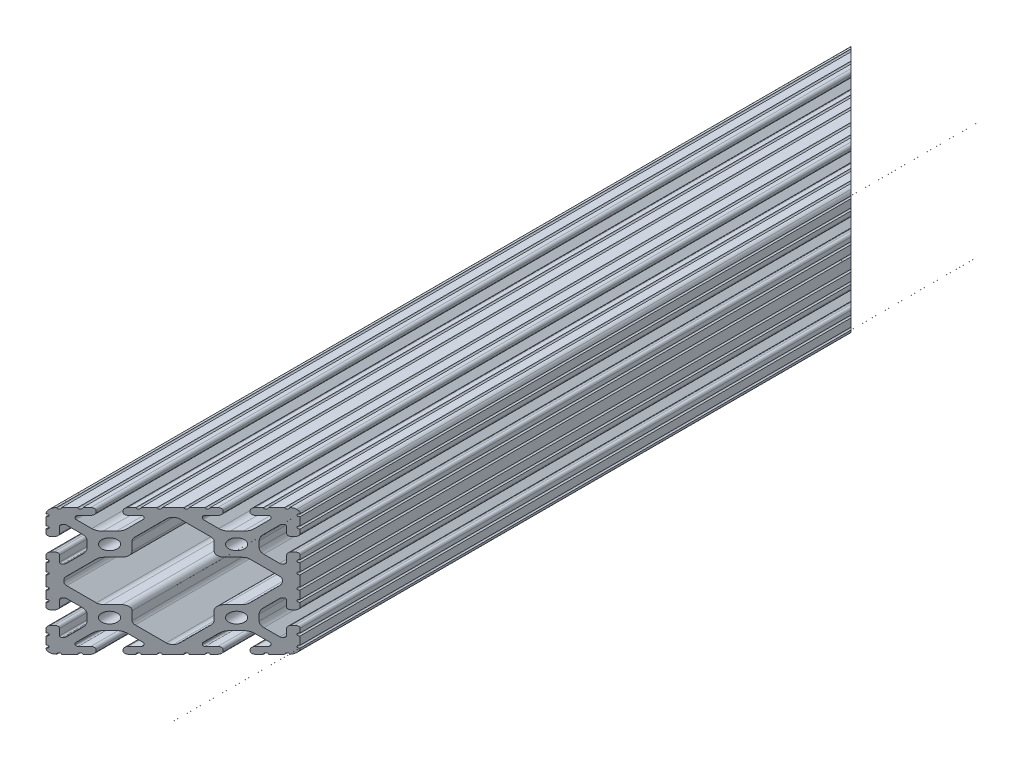
SolidWorks part; units mm, degrees
material "6061-T6 (SS)"
ref_plane "Front" through (0, 0, 0) normal (0, 0, 1) x (1, 0, 0)
ref_plane "Top" through (0, 0, 0) normal (0, 1, 0) x (1, 0, 0)
ref_plane "Right" through (0, 0, 0) normal (1, 0, 0) x (0, 0, -1)
ref_plane "Plane1" through (0, 0, -609.6) normal (0, 0, -1) x (-1, 0, 0)
sketch "Sketch1" plane through (0, 0, -609.6) normal (0, 0, -1) x (-1, 0, 0)
  line L0 (31.9021, -2.4756) -> (23.0141, -11.3637)
  line L1 (20.769, -12.2936) -> (15.4686, -12.2936)
  line L2 (12.2936, -15.4686) -> (12.2936, -20.5983)
  line L3 (11.3637, -22.8433) -> (2.0515, -32.1555)
  line L4 (-2.0515, -32.1555) -> (-11.3637, -22.8433)
  line L5 (-12.2936, -20.5983) -> (-12.2936, -15.4686)
  line L6 (-15.4686, -12.2936) -> (-20.769, -12.2936)
  line L7 (-23.0141, -11.3637) -> (-31.9021, -2.4756)
  line L8 (-31.9021, 2.4756) -> (-23.0141, 11.3637)
  line L9 (-20.769, 12.2936) -> (-15.4686, 12.2936)
  line L10 (-12.2936, 15.4686) -> (-12.2936, 20.5983)
  line L11 (-11.3637, 22.8433) -> (-2.0515, 32.1555)
  line L12 (2.0515, 32.1555) -> (11.3637, 22.8433)
  line L13 (12.2936, 20.5983) -> (12.2936, 15.4686)
  line L14 (15.4686, 12.2936) -> (20.769, 12.2936)
  line L15 (23.0141, 11.3637) -> (31.9021, 2.4756)
  line L16 (36.5252, -23.0554) -> (35.6108, -23.0554)
  line L17 (34.036, -24.6302) -> (34.036, -28.448)
  line L18 (33.147, -29.337) -> (32.6643, -29.337)
  line L19 (32.0357, -29.0766) -> (27.1976, -24.2385)
  line L20 (25.8064, -20.8799) -> (25.8064, -17.2201)
  line L21 (27.1976, -13.8615) -> (31.9489, -9.1101)
  line L22 (32.7869, -8.763) -> (33.0603, -8.763)
  line L23 (34.036, -9.7387) -> (34.036, -13.4698)
  line L24 (35.6108, -15.0446) -> (36.5252, -15.0446)
  line L25 (38.1, -13.4698) -> (38.1, -11.075)
  line L26 (38.1, -9.552) -> (38.1, -4.7238)
  line L27 (38.1, -3.2007) -> (38.1, 3.2007)
  line L28 (38.1, 4.7238) -> (38.1, 9.552)
  line L29 (38.1, 11.075) -> (38.1, 13.4698)
  line L30 (36.5252, 15.0446) -> (35.6108, 15.0446)
  line L31 (34.036, 13.4698) -> (34.036, 9.7387)
  line L32 (33.0603, 8.763) -> (32.7869, 8.763)
  line L33 (31.9489, 9.1101) -> (27.1976, 13.8615)
  line L34 (25.8064, 17.2201) -> (25.8064, 20.8799)
  line L35 (27.1976, 24.2385) -> (32.0357, 29.0766)
  line L36 (32.6643, 29.337) -> (33.147, 29.337)
  line L37 (34.036, 28.448) -> (34.036, 24.6302)
  line L38 (35.6108, 23.0554) -> (36.5252, 23.0554)
  line L39 (38.1, 24.6302) -> (38.1, 27.0238)
  line L40 (38.1, 28.5453) -> (38.1, 33.373)
  line L41 (33.4288, 38.1) -> (28.6011, 38.1)
  line L42 (27.0772, 38.1) -> (24.6888, 38.1)
  line L43 (23.114, 36.5252) -> (23.114, 35.6108)
  line L44 (24.6888, 34.036) -> (28.448, 34.036)
  line L45 (29.337, 33.147) -> (29.337, 32.7207)
  line L46 (29.1002, 31.8885) -> (24.4093, 27.1976)
  line L47 (21.0507, 25.8064) -> (17.0493, 25.8064)
  line L48 (13.6907, 27.1976) -> (9.0234, 31.8649)
  line L49 (8.763, 32.4935) -> (8.763, 33.147)
  line L50 (9.652, 34.036) -> (13.4112, 34.036)
  line L51 (14.986, 35.6108) -> (14.986, 36.5252)
  line L52 (13.4112, 38.1) -> (11.1289, 38.1)
  line L53 (9.6053, 38.1) -> (4.7773, 38.1)
  line L54 (3.2537, 38.1) -> (-3.2537, 38.1)
  line L55 (-4.7773, 38.1) -> (-9.6053, 38.1)
  line L56 (-11.1289, 38.1) -> (-13.4112, 38.1)
  line L57 (-14.986, 36.5252) -> (-14.986, 35.6108)
  line L58 (-13.4112, 34.036) -> (-9.652, 34.036)
  line L59 (-8.763, 33.147) -> (-8.763, 32.4935)
  line L60 (-9.0234, 31.8649) -> (-13.6907, 27.1976)
  line L61 (-17.0493, 25.8064) -> (-21.0507, 25.8064)
  line L62 (-24.4093, 27.1976) -> (-29.1002, 31.8885)
  line L63 (-29.337, 32.7207) -> (-29.337, 33.147)
  line L64 (-28.448, 34.036) -> (-24.6888, 34.036)
  line L65 (-23.114, 35.6108) -> (-23.114, 36.5252)
  line L66 (-24.6888, 38.1) -> (-27.0772, 38.1)
  line L67 (-28.6011, 38.1) -> (-33.4288, 38.1)
  line L68 (-38.1, 33.373) -> (-38.1, 28.5453)
  line L69 (-38.1, 27.0238) -> (-38.1, 24.6302)
  line L70 (-36.5252, 23.0554) -> (-35.6108, 23.0554)
  line L71 (-34.036, 24.6302) -> (-34.036, 28.448)
  line L72 (-33.147, 29.337) -> (-32.6643, 29.337)
  line L73 (-32.0357, 29.0766) -> (-27.1976, 24.2385)
  line L74 (-25.8064, 20.8799) -> (-25.8064, 17.2201)
  line L75 (-27.1976, 13.8615) -> (-31.9489, 9.1101)
  line L76 (-32.7869, 8.763) -> (-33.0603, 8.763)
  line L77 (-34.036, 9.7387) -> (-34.036, 13.4698)
  line L78 (-35.6108, 15.0446) -> (-36.5252, 15.0446)
  line L79 (-38.1, 13.4698) -> (-38.1, 11.075)
  line L80 (-38.1, 9.552) -> (-38.1, 4.7238)
  line L81 (-38.1, 3.2007) -> (-38.1, -3.2007)
  line L82 (-38.1, -4.7238) -> (-38.1, -9.552)
  line L83 (-38.1, -11.075) -> (-38.1, -13.4698)
  line L84 (-36.5252, -15.0446) -> (-35.6108, -15.0446)
  line L85 (-34.036, -13.4698) -> (-34.036, -9.7387)
  line L86 (-33.0603, -8.763) -> (-32.7869, -8.763)
  line L87 (-31.9489, -9.1101) -> (-27.1976, -13.8615)
  line L88 (-25.8064, -17.2201) -> (-25.8064, -20.8799)
  line L89 (-27.1976, -24.2385) -> (-32.0357, -29.0766)
  line L90 (-32.6643, -29.337) -> (-33.147, -29.337)
  line L91 (-34.036, -28.448) -> (-34.036, -24.6302)
  line L92 (-35.6108, -23.0554) -> (-36.5252, -23.0554)
  line L93 (-38.1, -24.6302) -> (-38.1, -27.0238)
  line L94 (-38.1, -28.5453) -> (-38.1, -33.373)
  line L95 (-33.4288, -38.1) -> (-28.6011, -38.1)
  line L96 (-27.0772, -38.1) -> (-24.6888, -38.1)
  line L97 (-23.114, -36.5252) -> (-23.114, -35.6108)
  line L98 (-24.6888, -34.036) -> (-28.448, -34.036)
  line L99 (-29.337, -33.147) -> (-29.337, -32.7207)
  line L100 (-29.1002, -31.8885) -> (-24.4093, -27.1976)
  line L101 (-21.0507, -25.8064) -> (-17.0493, -25.8064)
  line L102 (-13.6907, -27.1976) -> (-9.0234, -31.8649)
  line L103 (-8.763, -32.4935) -> (-8.763, -33.147)
  line L104 (-9.652, -34.036) -> (-13.4112, -34.036)
  line L105 (-14.986, -35.6108) -> (-14.986, -36.5252)
  line L106 (-13.4112, -38.1) -> (-11.1289, -38.1)
  line L107 (-9.6053, -38.1) -> (-4.7773, -38.1)
  line L108 (-3.2537, -38.1) -> (3.2537, -38.1)
  line L109 (4.7773, -38.1) -> (9.6053, -38.1)
  line L110 (11.1289, -38.1) -> (13.4112, -38.1)
  line L111 (14.986, -36.5252) -> (14.986, -35.6108)
  line L112 (13.4112, -34.036) -> (9.652, -34.036)
  line L113 (8.763, -33.147) -> (8.763, -32.4935)
  line L114 (9.0234, -31.8649) -> (13.6907, -27.1976)
  line L115 (17.0493, -25.8064) -> (21.0507, -25.8064)
  line L116 (24.4093, -27.1976) -> (29.1002, -31.8885)
  line L117 (29.337, -32.7207) -> (29.337, -33.147)
  line L118 (28.448, -34.036) -> (24.6888, -34.036)
  line L119 (23.114, -35.6108) -> (23.114, -36.5252)
  line L120 (24.6888, -38.1) -> (27.0772, -38.1)
  line L121 (28.6011, -38.1) -> (33.4288, -38.1)
  line L122 (38.1, -33.373) -> (38.1, -28.5453)
  line L123 (38.1, -27.0238) -> (38.1, -24.6302)
  arc A0 (31.9021, 2.4756) -> (32.7287, 0) centre (29.8367, 0.4102) cw
  arc A1 (32.7287, 0) -> (31.9021, -2.4756) centre (29.8367, -0.4102) cw
  arc A2 (23.0141, -11.3637) -> (20.769, -12.2936) centre (20.769, -9.1186) cw
  arc A3 (15.4686, -12.2936) -> (12.2936, -15.4686) centre (15.4686, -15.4686) ccw
  arc A4 (12.2936, -20.5983) -> (11.3637, -22.8433) centre (9.1186, -20.5983) cw
  arc A5 (2.0515, -32.1555) -> (0, -33.011) centre (-0.0139, -30.09) cw
  arc A6 (0, -33.011) -> (-2.0515, -32.1555) centre (0.0139, -30.09) cw
  arc A7 (-11.3637, -22.8433) -> (-12.2936, -20.5983) centre (-9.1186, -20.5983) cw
  arc A8 (-12.2936, -15.4686) -> (-15.4686, -12.2936) centre (-15.4686, -15.4686) ccw
  arc A9 (-20.769, -12.2936) -> (-23.0141, -11.3637) centre (-20.769, -9.1186) cw
  arc A10 (-31.9021, -2.4756) -> (-32.7287, 0) centre (-29.8367, -0.4102) cw
  arc A11 (-32.7287, 0) -> (-31.9021, 2.4756) centre (-29.8367, 0.4102) cw
  arc A12 (-23.0141, 11.3637) -> (-20.769, 12.2936) centre (-20.769, 9.1186) cw
  arc A13 (-15.4686, 12.2936) -> (-12.2936, 15.4686) centre (-15.4686, 15.4686) ccw
  arc A14 (-12.2936, 20.5983) -> (-11.3637, 22.8433) centre (-9.1186, 20.5983) cw
  arc A15 (-2.0515, 32.1555) -> (0, 33.011) centre (0.0139, 30.09) cw
  arc A16 (0, 33.011) -> (2.0515, 32.1555) centre (-0.0139, 30.09) cw
  arc A17 (11.3637, 22.8433) -> (12.2936, 20.5983) centre (9.1186, 20.5983) cw
  arc A18 (12.2936, 15.4686) -> (15.4686, 12.2936) centre (15.4686, 15.4686) ccw
  arc A19 (20.769, 12.2936) -> (23.0141, 11.3637) centre (20.769, 9.1186) cw
  circle A20 centre (19.05, -19.05) radius 3.3274
  circle A21 centre (19.05, 19.05) radius 3.3274
  circle A22 centre (-19.05, 19.05) radius 3.3274
  circle A23 centre (-19.05, -19.05) radius 3.3274
  arc A24 (38.1, -24.6302) -> (36.5252, -23.0554) centre (36.5252, -24.6302) ccw
  arc A25 (35.6108, -23.0554) -> (34.036, -24.6302) centre (35.6108, -24.6302) ccw
  arc A26 (34.036, -28.448) -> (33.147, -29.337) centre (33.147, -28.448) cw
  arc A27 (32.6643, -29.337) -> (32.0357, -29.0766) centre (32.6643, -28.448) cw
  arc A28 (27.1976, -24.2385) -> (25.8064, -20.8799) centre (30.5562, -20.8799) cw
  arc A29 (25.8064, -17.2201) -> (27.1976, -13.8615) centre (30.5562, -17.2201) cw
  arc A30 (31.9489, -9.1101) -> (32.7869, -8.763) centre (32.7869, -9.9481) cw
  arc A31 (33.0603, -8.763) -> (34.036, -9.7387) centre (33.0603, -9.7387) cw
  arc A32 (34.036, -13.4698) -> (35.6108, -15.0446) centre (35.6108, -13.4698) ccw
  arc A33 (36.5252, -15.0446) -> (38.1, -13.4698) centre (36.5252, -13.4698) ccw
  arc A34 (38.1, -11.075) -> (38.1, -9.552) centre (37.9035, -10.3135) cw
  arc A35 (38.1, -4.7238) -> (38.1, -3.2007) centre (37.9035, -3.9622) cw
  arc A36 (38.1, 3.2007) -> (38.1, 4.7238) centre (37.9035, 3.9622) cw
  arc A37 (38.1, 9.552) -> (38.1, 11.075) centre (37.9035, 10.3135) cw
  arc A38 (38.1, 13.4698) -> (36.5252, 15.0446) centre (36.5252, 13.4698) ccw
  arc A39 (35.6108, 15.0446) -> (34.036, 13.4698) centre (35.6108, 13.4698) ccw
  arc A40 (34.036, 9.7387) -> (33.0603, 8.763) centre (33.0603, 9.7387) cw
  arc A41 (32.7869, 8.763) -> (31.9489, 9.1101) centre (32.7869, 9.9481) cw
  arc A42 (27.1976, 13.8615) -> (25.8064, 17.2201) centre (30.5562, 17.2201) cw
  arc A43 (25.8064, 20.8799) -> (27.1976, 24.2385) centre (30.5562, 20.8799) cw
  arc A44 (32.0357, 29.0766) -> (32.6643, 29.337) centre (32.6643, 28.448) cw
  arc A45 (33.147, 29.337) -> (34.036, 28.448) centre (33.147, 28.448) cw
  arc A46 (34.036, 24.6302) -> (35.6108, 23.0554) centre (35.6108, 24.6302) ccw
  arc A47 (36.5252, 23.0554) -> (38.1, 24.6302) centre (36.5252, 24.6302) ccw
  arc A48 (38.1, 27.0238) -> (38.1, 28.5453) centre (37.9035, 27.7845) cw
  arc A49 (38.1, 33.373) -> (38.1, 34.8455) centre (37.9035, 34.1092) cw
  arc A50 (38.1, 34.8455) -> (37.0861, 37.1826) centre (34.925, 34.8566) ccw
  arc A51 (37.0861, 37.1826) -> (34.9527, 38.1) centre (34.8521, 34.9266) ccw
  arc A52 (34.9527, 38.1) -> (33.4288, 38.1) centre (34.1907, 38.0824) cw
  arc A53 (28.6011, 38.1) -> (27.0772, 38.1) centre (27.8392, 38.0824) cw
  arc A54 (24.6888, 38.1) -> (23.114, 36.5252) centre (24.6888, 36.5252) ccw
  arc A55 (23.114, 35.6108) -> (24.6888, 34.036) centre (24.6888, 35.6108) ccw
  arc A56 (28.448, 34.036) -> (29.337, 33.147) centre (28.448, 33.147) cw
  arc A57 (29.337, 32.7207) -> (29.1002, 31.8885) centre (28.4716, 32.5172) cw
  arc A58 (24.4093, 27.1976) -> (21.0507, 25.8064) centre (21.0507, 30.5562) cw
  arc A59 (17.0493, 25.8064) -> (13.6907, 27.1976) centre (17.0493, 30.5562) cw
  arc A60 (9.0234, 31.8649) -> (8.763, 32.4935) centre (9.652, 32.4935) cw
  arc A61 (8.763, 33.147) -> (9.652, 34.036) centre (9.652, 33.147) cw
  arc A62 (13.4112, 34.036) -> (14.986, 35.6108) centre (13.4112, 35.6108) ccw
  arc A63 (14.986, 36.5252) -> (13.4112, 38.1) centre (13.4112, 36.5252) ccw
  arc A64 (11.1289, 38.1) -> (9.6053, 38.1) centre (10.3671, 38.0824) cw
  arc A65 (4.7773, 38.1) -> (3.2537, 38.1) centre (4.0155, 38.0824) cw
  arc A66 (-3.2537, 38.1) -> (-4.7773, 38.1) centre (-4.0155, 38.0824) cw
  arc A67 (-9.6053, 38.1) -> (-11.1289, 38.1) centre (-10.3671, 38.0824) cw
  arc A68 (-13.4112, 38.1) -> (-14.986, 36.5252) centre (-13.4112, 36.5252) ccw
  arc A69 (-14.986, 35.6108) -> (-13.4112, 34.036) centre (-13.4112, 35.6108) ccw
  arc A70 (-9.652, 34.036) -> (-8.763, 33.147) centre (-9.652, 33.147) cw
  arc A71 (-8.763, 32.4935) -> (-9.0234, 31.8649) centre (-9.652, 32.4935) cw
  arc A72 (-13.6907, 27.1976) -> (-17.0493, 25.8064) centre (-17.0493, 30.5562) cw
  arc A73 (-21.0507, 25.8064) -> (-24.4093, 27.1976) centre (-21.0507, 30.5562) cw
  arc A74 (-29.1002, 31.8885) -> (-29.337, 32.7207) centre (-28.4716, 32.5172) cw
  arc A75 (-29.337, 33.147) -> (-28.448, 34.036) centre (-28.448, 33.147) cw
  arc A76 (-24.6888, 34.036) -> (-23.114, 35.6108) centre (-24.6888, 35.6108) ccw
  arc A77 (-23.114, 36.5252) -> (-24.6888, 38.1) centre (-24.6888, 36.5252) ccw
  arc A78 (-27.0772, 38.1) -> (-28.6011, 38.1) centre (-27.8392, 38.0824) cw
  arc A79 (-33.4288, 38.1) -> (-34.9527, 38.1) centre (-34.1907, 38.0824) cw
  arc A80 (-34.9527, 38.1) -> (-37.0861, 37.1826) centre (-34.8521, 34.9266) ccw
  arc A81 (-37.0861, 37.1826) -> (-38.1, 34.8455) centre (-34.925, 34.8566) ccw
  arc A82 (-38.1, 34.8455) -> (-38.1, 33.373) centre (-37.9035, 34.1092) cw
  arc A83 (-38.1, 28.5453) -> (-38.1, 27.0238) centre (-37.9035, 27.7845) cw
  arc A84 (-38.1, 24.6302) -> (-36.5252, 23.0554) centre (-36.5252, 24.6302) ccw
  arc A85 (-35.6108, 23.0554) -> (-34.036, 24.6302) centre (-35.6108, 24.6302) ccw
  arc A86 (-34.036, 28.448) -> (-33.147, 29.337) centre (-33.147, 28.448) cw
  arc A87 (-32.6643, 29.337) -> (-32.0357, 29.0766) centre (-32.6643, 28.448) cw
  arc A88 (-27.1976, 24.2385) -> (-25.8064, 20.8799) centre (-30.5562, 20.8799) cw
  arc A89 (-25.8064, 17.2201) -> (-27.1976, 13.8615) centre (-30.5562, 17.2201) cw
  arc A90 (-31.9489, 9.1101) -> (-32.7869, 8.763) centre (-32.7869, 9.9481) cw
  arc A91 (-33.0603, 8.763) -> (-34.036, 9.7387) centre (-33.0603, 9.7387) cw
  arc A92 (-34.036, 13.4698) -> (-35.6108, 15.0446) centre (-35.6108, 13.4698) ccw
  arc A93 (-36.5252, 15.0446) -> (-38.1, 13.4698) centre (-36.5252, 13.4698) ccw
  arc A94 (-38.1, 11.075) -> (-38.1, 9.552) centre (-37.9035, 10.3135) cw
  arc A95 (-38.1, 4.7238) -> (-38.1, 3.2007) centre (-37.9035, 3.9622) cw
  arc A96 (-38.1, -3.2007) -> (-38.1, -4.7238) centre (-37.9035, -3.9622) cw
  arc A97 (-38.1, -9.552) -> (-38.1, -11.075) centre (-37.9035, -10.3135) cw
  arc A98 (-38.1, -13.4698) -> (-36.5252, -15.0446) centre (-36.5252, -13.4698) ccw
  arc A99 (-35.6108, -15.0446) -> (-34.036, -13.4698) centre (-35.6108, -13.4698) ccw
  arc A100 (-34.036, -9.7387) -> (-33.0603, -8.763) centre (-33.0603, -9.7387) cw
  arc A101 (-32.7869, -8.763) -> (-31.9489, -9.1101) centre (-32.7869, -9.9481) cw
  arc A102 (-27.1976, -13.8615) -> (-25.8064, -17.2201) centre (-30.5562, -17.2201) cw
  arc A103 (-25.8064, -20.8799) -> (-27.1976, -24.2385) centre (-30.5562, -20.8799) cw
  arc A104 (-32.0357, -29.0766) -> (-32.6643, -29.337) centre (-32.6643, -28.448) cw
  arc A105 (-33.147, -29.337) -> (-34.036, -28.448) centre (-33.147, -28.448) cw
  arc A106 (-34.036, -24.6302) -> (-35.6108, -23.0554) centre (-35.6108, -24.6302) ccw
  arc A107 (-36.5252, -23.0554) -> (-38.1, -24.6302) centre (-36.5252, -24.6302) ccw
  arc A108 (-38.1, -27.0238) -> (-38.1, -28.5453) centre (-37.9035, -27.7845) cw
  arc A109 (-38.1, -33.373) -> (-38.1, -34.8455) centre (-37.9035, -34.1092) cw
  arc A110 (-38.1, -34.8455) -> (-37.0861, -37.1826) centre (-34.925, -34.8566) ccw
  arc A111 (-37.0861, -37.1826) -> (-34.9527, -38.1) centre (-34.8521, -34.9266) ccw
  arc A112 (-34.9527, -38.1) -> (-33.4288, -38.1) centre (-34.1907, -38.0824) cw
  arc A113 (-28.6011, -38.1) -> (-27.0772, -38.1) centre (-27.8392, -38.0824) cw
  arc A114 (-24.6888, -38.1) -> (-23.114, -36.5252) centre (-24.6888, -36.5252) ccw
  arc A115 (-23.114, -35.6108) -> (-24.6888, -34.036) centre (-24.6888, -35.6108) ccw
  arc A116 (-28.448, -34.036) -> (-29.337, -33.147) centre (-28.448, -33.147) cw
  arc A117 (-29.337, -32.7207) -> (-29.1002, -31.8885) centre (-28.4716, -32.5172) cw
  arc A118 (-24.4093, -27.1976) -> (-21.0507, -25.8064) centre (-21.0507, -30.5562) cw
  arc A119 (-17.0493, -25.8064) -> (-13.6907, -27.1976) centre (-17.0493, -30.5562) cw
  arc A120 (-9.0234, -31.8649) -> (-8.763, -32.4935) centre (-9.652, -32.4935) cw
  arc A121 (-8.763, -33.147) -> (-9.652, -34.036) centre (-9.652, -33.147) cw
  arc A122 (-13.4112, -34.036) -> (-14.986, -35.6108) centre (-13.4112, -35.6108) ccw
  arc A123 (-14.986, -36.5252) -> (-13.4112, -38.1) centre (-13.4112, -36.5252) ccw
  arc A124 (-11.1289, -38.1) -> (-9.6053, -38.1) centre (-10.3671, -38.0824) cw
  arc A125 (-4.7773, -38.1) -> (-3.2537, -38.1) centre (-4.0155, -38.0824) cw
  arc A126 (3.2537, -38.1) -> (4.7773, -38.1) centre (4.0155, -38.0824) cw
  arc A127 (9.6053, -38.1) -> (11.1289, -38.1) centre (10.3671, -38.0824) cw
  arc A128 (13.4112, -38.1) -> (14.986, -36.5252) centre (13.4112, -36.5252) ccw
  arc A129 (14.986, -35.6108) -> (13.4112, -34.036) centre (13.4112, -35.6108) ccw
  arc A130 (9.652, -34.036) -> (8.763, -33.147) centre (9.652, -33.147) cw
  arc A131 (8.763, -32.4935) -> (9.0234, -31.8649) centre (9.652, -32.4935) cw
  arc A132 (13.6907, -27.1976) -> (17.0493, -25.8064) centre (17.0493, -30.5562) cw
  arc A133 (21.0507, -25.8064) -> (24.4093, -27.1976) centre (21.0507, -30.5562) cw
  arc A134 (29.1002, -31.8885) -> (29.337, -32.7207) centre (28.4716, -32.5172) cw
  arc A135 (29.337, -33.147) -> (28.448, -34.036) centre (28.448, -33.147) cw
  arc A136 (24.6888, -34.036) -> (23.114, -35.6108) centre (24.6888, -35.6108) ccw
  arc A137 (23.114, -36.5252) -> (24.6888, -38.1) centre (24.6888, -36.5252) ccw
  arc A138 (27.0772, -38.1) -> (28.6011, -38.1) centre (27.8392, -38.0824) cw
  arc A139 (33.4288, -38.1) -> (34.9527, -38.1) centre (34.1907, -38.0824) cw
  arc A140 (34.9527, -38.1) -> (37.0861, -37.1826) centre (34.8521, -34.9266) ccw
  arc A141 (37.0861, -37.1826) -> (38.1, -34.8455) centre (34.925, -34.8566) ccw
  arc A142 (38.1, -34.8455) -> (38.1, -33.373) centre (37.9035, -34.1092) cw
  arc A143 (38.1, -28.5453) -> (38.1, -27.0238) centre (37.9035, -27.7845) cw
extrude "Boss-Extrude1" add sketch "Sketch1" against normal blind 482.6
sketch "Sketch3" plane through (0, 38.1, 0) normal (0, 1, 0) x (1, 0, 0)
  line L0 (-38.1, 609.6) -> (38.1, 609.6)
  line L1 (38.1, 609.6) -> (38.1, 533.4)
  line L2 (38.1, 533.4) -> (-38.1, 609.6)
  line L3 (28.6011, 609.6) -> (33.4288, 609.6) construction
  line L4 (38.1, 127) -> (38.1, 609.6) construction
  dimension "D1" = 76.2
  dimension "D2" = 76.2
  dimension "D3" = 0
  dimension "D4" = 0
extrude "Cut-Extrude1" cut sketch "Sketch3" against normal through all
sketch "Sketch6" plane through (0, 38.1, 0) normal (0, 1, 0) x (1, 0, 0)
  line L0 (-38.1, 127) -> (38.1, 127)
  line L1 (38.1, 127) -> (38.1, 203.2)
  line L2 (38.1, 203.2) -> (-38.1, 127)
  line L3 (4.7773, 127) -> (9.6053, 127) construction
  line L5 (38.1, 127) -> (38.1, 533.4) construction
  point P2 (0, 127)
  dimension "D1" = 76.2
  dimension "D2" = 76.2
  dimension "D3" = 0
  dimension "D4" = 0
extrude "Cut-Extrude2" cut sketch "Sketch6" against normal through all
